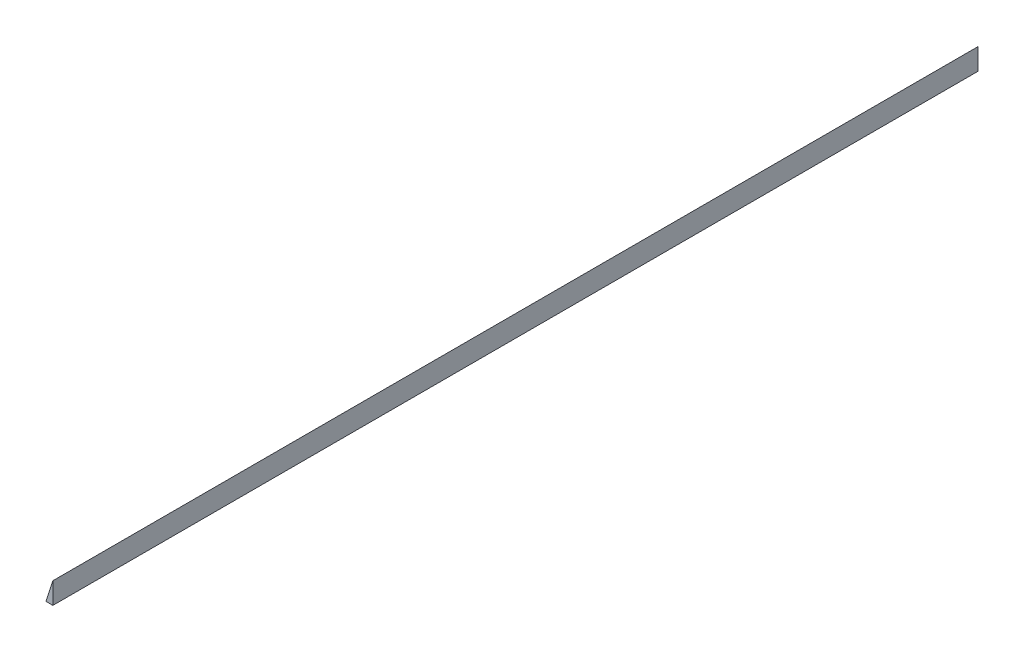
SolidWorks part; units mm, degrees
ref_plane "Front Plane" through (0, 0, 0) normal (0, 0, 1) x (1, 0, 0)
ref_plane "Top Plane" through (0, 0, 0) normal (0, 1, 0) x (1, 0, 0)
ref_plane "Right Plane" through (0, 0, 0) normal (1, 0, 0) x (0, 0, -1)
sketch "Sketch1" plane through (0, 0, 0) normal (0, 0, 1) x (1, 0, 0)
  line L0 (0, 0) -> (1.5305, 4.76)
  line L1 (1.5305, 4.76) -> (1.5305, 0)
  line L2 (1.5305, 0) -> (0, 0)
  dimension "D1" = 5
  dimension "D2" = 4.76
extrude "Boss-Extrude1" add sketch "Sketch1" along normal blind 206
